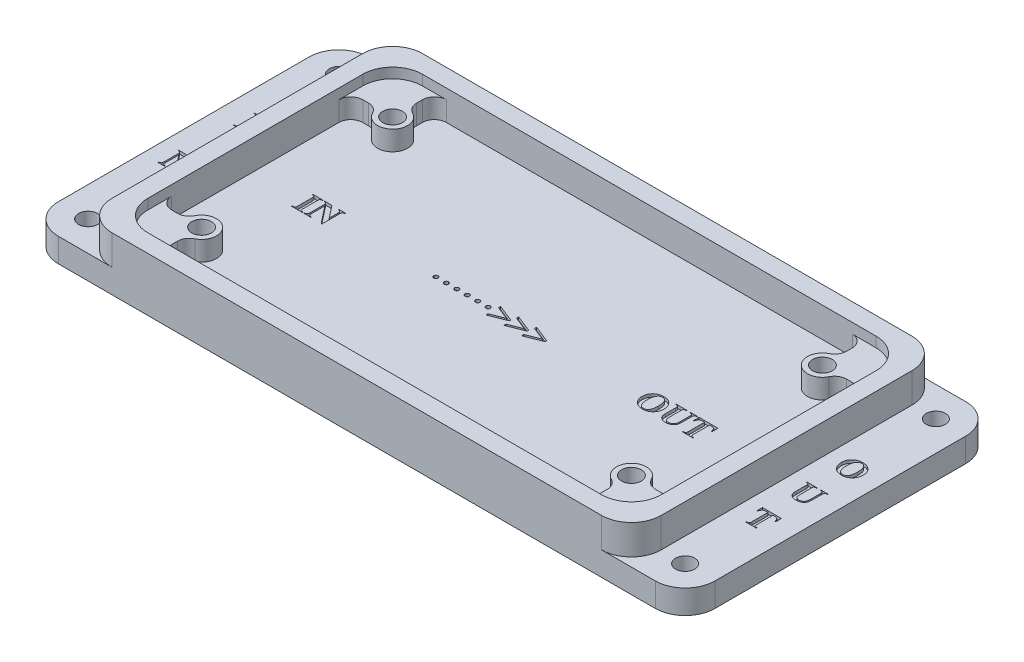
SolidWorks part; units mm, degrees
material "ABS"
ref_plane "前视基准面" through (0, 0, 0) normal (0, 0, 1) x (1, 0, 0)
ref_plane "上视基准面" through (0, 0, 0) normal (0, 1, 0) x (1, 0, 0)
ref_plane "右视基准面" through (0, 0, 0) normal (1, 0, 0) x (0, 0, -1)
other "Configuration Table"
sketch "草图1" plane through (0, 0, 0) normal (0, 1, 0) x (1, 0, 0)
  line L0 (-46, 26) -> (-46, -26)
  line L1 (-43, 23) -> (43, 23)
  line L2 (-43, 23) -> (-43, -23)
  line L3 (-43, -23) -> (43, -23)
  line L4 (43, 23) -> (43, -23)
  line L5 (-43, 23) -> (43, -23) construction
  line L6 (-43, -23) -> (43, 23) construction
  line L7 (-46, -26) -> (46, -26)
  line L8 (46, 26) -> (46, -26)
  line L9 (-46, 26) -> (46, 26)
  point P0 (0, 0)
  dimension "D1" = 46
  dimension "D2" = 86
  dimension "D3" = 3
extrude "凸台-拉伸1" add sketch "草图1" along normal blind 5
sketch "草图2" plane through (0, 0, 0) normal (0, -1, 0) x (1, 0, 0)
  line L0 (-38.5, 16) -> (-43, 16)
  line L1 (-36, 16) -> (36, 16) construction
  line L2 (-36, 16) -> (-36, -16) construction
  line L3 (-36, -16) -> (36, -16) construction
  line L4 (36, 16) -> (36, -16) construction
  line L5 (-36, 16) -> (36, -16) construction
  line L6 (-36, -16) -> (36, 16) construction
  line L7 (-43, -23) -> (-43, 23) construction
  line L8 (-36, 16) -> (-36, 17.65)
  line L9 (-43, 23) -> (43, 23) construction
  line L10 (-38.5, -16) -> (-43, -16)
  line L11 (-36, -18.5) -> (-36, -23)
  line L12 (43, -23) -> (-43, -23) construction
  line L13 (36, -18.5) -> (36, -23)
  line L14 (38.5, -16) -> (43, -16)
  line L15 (43, 23) -> (43, -23) construction
  line L16 (36, 18.5) -> (36, 23)
  line L17 (38.5, 16) -> (43, 16)
  line L18 (43, 23) -> (43, 16)
  line L19 (43, -23) -> (36, -23)
  line L20 (-43, -23) -> (-43, -16)
  line L21 (-43, 23) -> (-36, 23)
  line L22 (36, 23) -> (43, 23)
  line L23 (-43, 16) -> (-43, 23)
  line L24 (-36, -23) -> (-43, -23)
  line L25 (43, -16) -> (43, -23)
  line L26 (-36, 18.5) -> (-36, 23)
  arc A0 (-38.5, 16) -> (-36, 18.5) centre (-36, 16) ccw
  arc A1 (36, 18.5) -> (38.5, 16) centre (36, 16) ccw
  arc A2 (38.5, -16) -> (36, -18.5) centre (36, -16) ccw
  arc A3 (-36, -18.5) -> (-38.5, -16) centre (-36, -16) ccw
  circle A4 centre (-36, -16) radius 1.65
  circle A5 centre (36, -16) radius 1.65
  circle A6 centre (36, 16) radius 1.65
  circle A7 centre (-36, 16) radius 1.65
  point P0 (0, 0)
  line M5 (-43, 23) -> (43, 23)
  line M6 (43, 23) -> (43, -23)
  line M7 (43, -23) -> (-43, -23)
  line M8 (-43, -23) -> (-43, 23)
  dimension "D3" = 5
  dimension "D4" = 3.3
  dimension "D1" = 32
  dimension "D2" = 72
extrude "凸台-拉伸3" add sketch "草图2" against normal up to surface (5 mm away) contours L16 A1 L17 A6 M6 M5 | L14 A2 L13 A5 M7 M6 | L11 A3 L10 A4 M8 M7 | L0 A0 L26 A7 M5 M8 up to face at (0, 5, 0)
fillet "圆角1" radius 2 16 edges at (38.5, 2.5, 16) (43, 2.5, 16) (43, 2.5, -16) (38.5, 2.5, -16) (36, 2.5, -18.5) (36, 2.5, -23) (-36, 2.5, -23) (-36, 2.5, -18.5) (-38.5, 2.5, -16) (-43, 2.5, -16) (-43, 2.5, 16) (-38.5, 2.5, 16) (-36, 2.5, 18.5) (-36, 2.5, 23) (36, 2.5, 23) (36, 2.5, 18.5)
fillet "圆角2" radius 5 4 edges at (-46, 2.5, 26) (46, 2.5, 26) (46, 2.5, -26) (-46, 2.5, -26)
sketch "草图3" plane through (0, 5, 0) normal (0, 1, 0) x (1, 0, 0)
  line L0 (-43, 14) -> (-43, -14) construction
  line L1 (-43, 23) -> (43, 23)
  line L2 (-43, 23) -> (-43, -23)
  line L3 (-43, -23) -> (43, -23)
  line L4 (43, 23) -> (43, -23)
  line L5 (-43, 23) -> (43, -23) construction
  line L6 (-43, -23) -> (43, 23) construction
  line L7 (34, 23) -> (-34, 23) construction
  point P0 (0, 0)
extrude "切除-拉伸1" cut sketch "草图3" against normal blind 1.7
sketch "草图5" plane through (0, 0, 0) normal (0, -1, 0) x (1, 0, 0)
  line L0 (-41, 26) -> (41, 26) construction
  line L1 (-55, 26) -> (55, 26)
  line L2 (-55, 26) -> (-55, -26)
  line L3 (-55, -26) -> (55, -26)
  line L4 (55, 26) -> (55, -26)
  line L5 (-55, 26) -> (55, -26) construction
  line L6 (-55, -26) -> (55, 26) construction
  line L8 (-46, -21) -> (-46, 21) construction
  line L9 (-50, 21) -> (50, 21) construction
  line L10 (-50, 21) -> (-50, -21) construction
  line L11 (-50, -21) -> (50, -21) construction
  line L12 (50, 21) -> (50, -21) construction
  line L13 (-50, 21) -> (50, -21) construction
  line L14 (-50, -21) -> (50, 21) construction
  circle A1 centre (-50, 21) radius 1.6
  circle A2 centre (-50, -21) radius 1.6
  circle A3 centre (50, -21) radius 1.6
  circle A4 centre (50, 21) radius 1.6
  point P0 (0, 0)
  point P8 (0, 0)
  dimension "D2" = 5
  dimension "D5" = 3.2
  dimension "D1" = 110
  dimension "D3" = 5
  dimension "D4" = 4
extrude "凸台-拉伸4" add sketch "草图5" along normal blind 4
sketch "草图6" plane through (0, -4, 0) normal (0, -1, 0) x (1, 0, 0)
  line L1 (-36, 16) -> (36, 16) construction
  line L2 (-36, 16) -> (-36, -16) construction
  line L3 (-36, -16) -> (36, -16) construction
  line L4 (36, 16) -> (36, -16) construction
  line L5 (-36, 16) -> (36, -16) construction
  line L6 (-36, -16) -> (36, 16) construction
  circle A0 centre (-36, 16) radius 3
  circle A1 centre (-36, -16) radius 3
  circle A2 centre (36, -16) radius 3
  circle A3 centre (36, 16) radius 3
  point P0 (0, 0)
  dimension "D3" = 6
  dimension "D1" = 32
  dimension "D2" = 72
extrude "切除-拉伸2" cut sketch "草图6" against normal blind 3
fillet "圆角3" radius 5 8 edges at (43, 4.15, -23) (43, 4.15, 23) (-43, 4.15, 23) (-43, 4.15, -23) (55, -2, 26) (55, -2, -26) (-55, -2, -26) (-55, -2, 26)
sketch "草图7" plane through (0, 0, 0) normal (0, 1, 0) x (1, 0, 0)
  text T0 "<b>I</b>" font "Times New Roman" height 3.5
  text T1 "<b>N</b>" font "Times New Roman" height 3.5
  text T2 "<b>O</b>\r\n<b>U</b>\r\n<b>T</b>"
  text T3 "<b>IN            ······>>>            OUT</b>\r\n"
extrude "切除-拉伸3" cut sketch "草图7" against normal blind 0.5
sketch "草图8" plane through (0, 0, 0) normal (0, 1, 0) x (1, 0, 0)
  circle A0 centre (-36, -16) radius 1.65
  circle A1 centre (-36, 16) radius 1.65
  circle A2 centre (36, 16) radius 1.65
  circle A3 centre (36, -16) radius 1.65
  circle A4 centre (-36, -16) radius 1.65 construction
  circle A7 centre (36, -16) radius 1.65 construction
  circle A8 centre (36, 16) radius 1.65 construction
  circle A9 centre (-36, 16) radius 1.65 construction
extrude "切除-拉伸4" cut sketch "草图8" against normal through all
